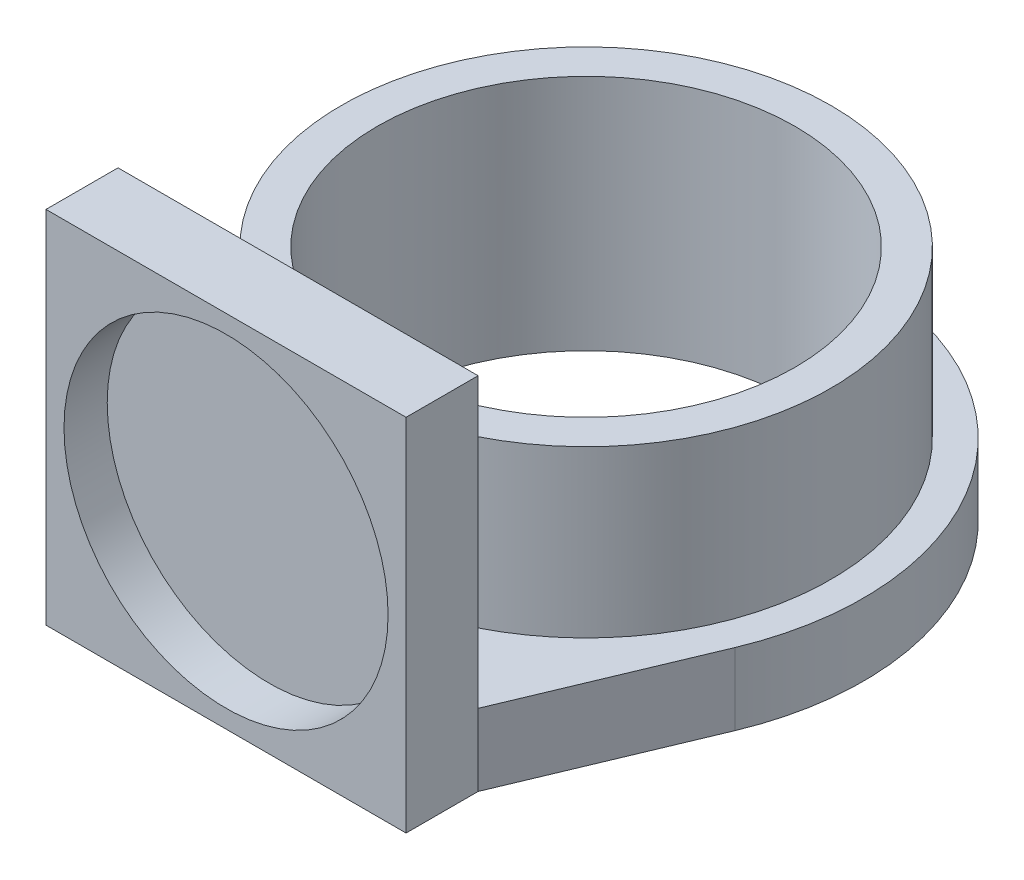
SolidWorks part; units mm, degrees
ref_plane "前视基准面" through (0, 0, 0) normal (0, 0, 1) x (1, 0, 0)
ref_plane "上视基准面" through (0, 0, 0) normal (0, 1, 0) x (1, 0, 0)
ref_plane "右视基准面" through (0, 0, 0) normal (1, 0, 0) x (0, 0, -1)
other "Configuration Table"
sketch "草图1" plane through (0, 0, 0) normal (0, 0, 1) x (1, 0, 0)
  line L1 (-25, -25) -> (25, -25)
  line L2 (-25, -25) -> (-25, 25)
  line L3 (-25, 25) -> (25, 25)
  line L4 (25, -25) -> (25, 25)
  line L5 (-25, -25) -> (25, 25) construction
  line L6 (-25, 25) -> (25, -25) construction
  point P0 (0, 0)
  dimension "D1" = 50
  dimension "D2" = 50
extrude "凸台-拉伸1" add sketch "草图1" along normal blind 10
sketch "草图2" plane through (0, -25, 0) normal (0, -1, 0) x (1, 0, 0)
  line L0 (0, 0) -> (0, -40) construction
  line L1 (-25, 0) -> (25, 0) construction
  line L2 (-25, 0) -> (-35.5175, -25.1422)
  line L3 (25, 0) -> (35.5175, -25.1422)
  line L4 (-25, 0) -> (25, 0)
  circle A0 centre (0, -40) radius 29
  arc A1 (-35.5175, -25.1422) -> (35.5175, -25.1422) centre (0, -40) ccw
  dimension "D1" = 58
  dimension "D3" = 77
  dimension "D2" = 40
extrude "凸台-拉伸2" add sketch "草图2" against normal blind 10
sketch "草图3" plane through (0, 0, 10) normal (0, 0, 1) x (1, 0, 0)
  circle A0 centre (0, 0) radius 22.5
  dimension "D1" = 45
extrude "切除-拉伸1" cut sketch "草图3" against normal blind 6
sketch "草图4" plane through (0, -15, 0) normal (0, 1, 0) x (1, 0, 0)
  circle A0 centre (0, 40) radius 29
  circle A1 centre (0, 40) radius 34
  dimension "D1" = 68
extrude "凸台-拉伸3" add sketch "草图4" along normal blind 23
